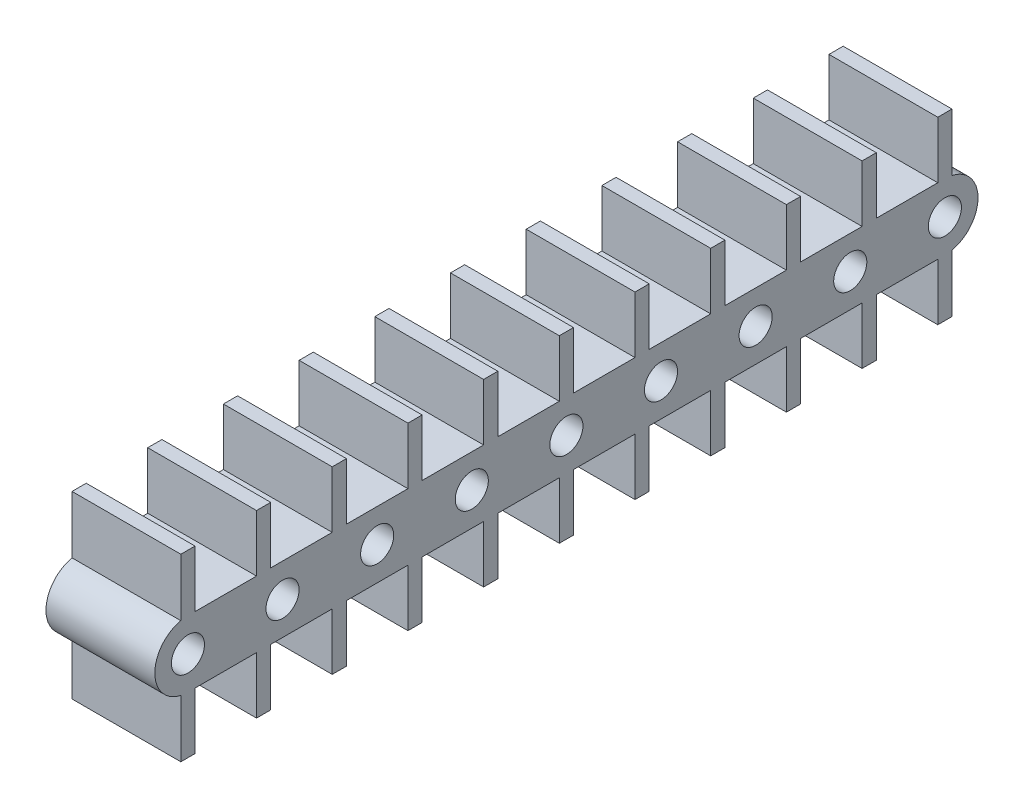
SolidWorks part; units mm, degrees
ref_plane "Front" through (0, 0, 0) normal (0, 0, 1) x (1, 0, 0)
ref_plane "Top" through (0, 0, 0) normal (0, 1, 0) x (1, 0, 0)
ref_plane "Right" through (0, 0, 0) normal (1, 0, 0) x (0, 0, -1)
sketch "Sketch1" plane through (0, 0, 0) normal (1, 0, 0) x (0, 0, -1)
  line L0 (0, 0) -> (800, 0) construction
  line L1 (7.5, 35) -> (72.5, 35)
  line L2 (7.5, -35) -> (72.5, -35)
  line L3 (400, 35) -> (400, -35) construction
  line L4 (407.5, 35) -> (472.5, 35)
  line L6 (392.5, 35) -> (392.5, 95)
  line L7 (392.5, 95) -> (407.5, 95)
  line L8 (407.5, 35) -> (407.5, 95)
  line L9 (487.5, 35) -> (487.5, 95)
  line L10 (472.5, 95) -> (487.5, 95)
  line L11 (472.5, 35) -> (472.5, 95)
  line L12 (567.5, 35) -> (567.5, 95)
  line L13 (552.5, 95) -> (567.5, 95)
  line L14 (552.5, 35) -> (552.5, 95)
  line L15 (647.5, 35) -> (647.5, 95)
  line L16 (632.5, 95) -> (647.5, 95)
  line L17 (632.5, 35) -> (632.5, 95)
  line L18 (727.5, 35) -> (727.5, 95)
  line L19 (712.5, 95) -> (727.5, 95)
  line L20 (712.5, 35) -> (712.5, 95)
  line L21 (807.5, 34.187) -> (807.5, 95)
  line L22 (792.5, 95) -> (807.5, 95)
  line L23 (792.5, 35) -> (792.5, 95)
  line L24 (327.5, 35) -> (327.5, 95)
  line L25 (312.5, 95) -> (327.5, 95)
  line L26 (312.5, 35) -> (312.5, 95)
  line L27 (247.5, 35) -> (247.5, 95)
  line L28 (232.5, 95) -> (247.5, 95)
  line L29 (232.5, 35) -> (232.5, 95)
  line L30 (167.5, 35) -> (167.5, 95)
  line L31 (152.5, 95) -> (167.5, 95)
  line L32 (152.5, 35) -> (152.5, 95)
  line L33 (87.5, 35) -> (87.5, 95)
  line L34 (72.5, 95) -> (87.5, 95)
  line L35 (72.5, 35) -> (72.5, 95)
  line L36 (7.5, 35) -> (7.5, 95)
  line L37 (-7.5, 95) -> (7.5, 95)
  line L38 (-7.5, 34.187) -> (-7.5, 95)
  line L39 (792.5, -35) -> (792.5, -95)
  line L40 (792.5, -95) -> (807.5, -95)
  line L41 (807.5, -34.187) -> (807.5, -95)
  line L42 (712.5, -35) -> (712.5, -95)
  line L43 (712.5, -95) -> (727.5, -95)
  line L44 (727.5, -35) -> (727.5, -95)
  line L45 (632.5, -35) -> (632.5, -95)
  line L46 (632.5, -95) -> (647.5, -95)
  line L47 (647.5, -35) -> (647.5, -95)
  line L48 (552.5, -35) -> (552.5, -95)
  line L49 (552.5, -95) -> (567.5, -95)
  line L50 (567.5, -35) -> (567.5, -95)
  line L51 (472.5, -35) -> (472.5, -95)
  line L52 (472.5, -95) -> (487.5, -95)
  line L53 (487.5, -35) -> (487.5, -95)
  line L54 (407.5, -35) -> (407.5, -95)
  line L55 (392.5, -95) -> (407.5, -95)
  line L56 (392.5, -35) -> (392.5, -95)
  line L57 (312.5, -35) -> (312.5, -95)
  line L58 (327.5, -35) -> (327.5, -95)
  line L59 (312.5, -95) -> (327.5, -95)
  line L60 (247.5, -35) -> (247.5, -95)
  line L61 (232.5, -95) -> (247.5, -95)
  line L62 (232.5, -35) -> (232.5, -95)
  line L63 (167.5, -35) -> (167.5, -95)
  line L64 (152.5, -95) -> (167.5, -95)
  line L65 (152.5, -35) -> (152.5, -95)
  line L66 (87.5, -35) -> (87.5, -95)
  line L67 (72.5, -95) -> (87.5, -95)
  line L68 (72.5, -35) -> (72.5, -95)
  line L69 (7.5, -35) -> (7.5, -95)
  line L70 (-7.5, -95) -> (7.5, -95)
  line L71 (-7.5, -34.187) -> (-7.5, -95)
  line L72 (87.5, -35) -> (152.5, -35)
  line L73 (167.5, -35) -> (232.5, -35)
  line L74 (247.5, -35) -> (312.5, -35)
  line L75 (87.5, 35) -> (152.5, 35)
  line L76 (167.5, 35) -> (232.5, 35)
  line L77 (407.5, -35) -> (472.5, -35)
  line L78 (327.5, -35) -> (392.5, -35)
  line L79 (487.5, -35) -> (552.5, -35)
  line L80 (487.5, 35) -> (552.5, 35)
  line L81 (567.5, 35) -> (632.5, 35)
  line L82 (567.5, -35) -> (632.5, -35)
  line L83 (647.5, 35) -> (712.5, 35)
  line L84 (647.5, -35) -> (712.5, -35)
  line L85 (727.5, -35) -> (792.5, -35)
  line L86 (727.5, 35) -> (792.5, 35)
  line L87 (327.5, 35) -> (392.5, 35)
  line L88 (247.5, 35) -> (312.5, 35)
  arc A0 (-7.5, 34.187) -> (-7.5, -34.187) centre (0, 0) ccw
  arc A1 (807.5, -34.187) -> (807.5, 34.187) centre (800, 0) ccw
  circle A2 centre (0, 0) radius 17.5
  circle A3 centre (800, 0) radius 17.5
  circle A4 centre (100, 0) radius 17.5
  circle A5 centre (200, 0) radius 17.5
  circle A6 centre (300, 0) radius 17.5
  circle A7 centre (400, 0) radius 17.5
  circle A8 centre (500, 0) radius 17.5
  circle A9 centre (600, 0) radius 17.5
  circle A10 centre (700, 0) radius 17.5
  point P3 (400, 0)
  point P32 (400, 95)
  dimension "D1" = 800
  dimension "D2" = 35
  dimension "D5" = 60
  dimension "D6" = 15
  dimension "D7" = 6
  dimension "D4" = 8
  dimension "D8" = 6
extrude "Boss-Extrude1" add sketch "Sketch1" along normal blind 115
